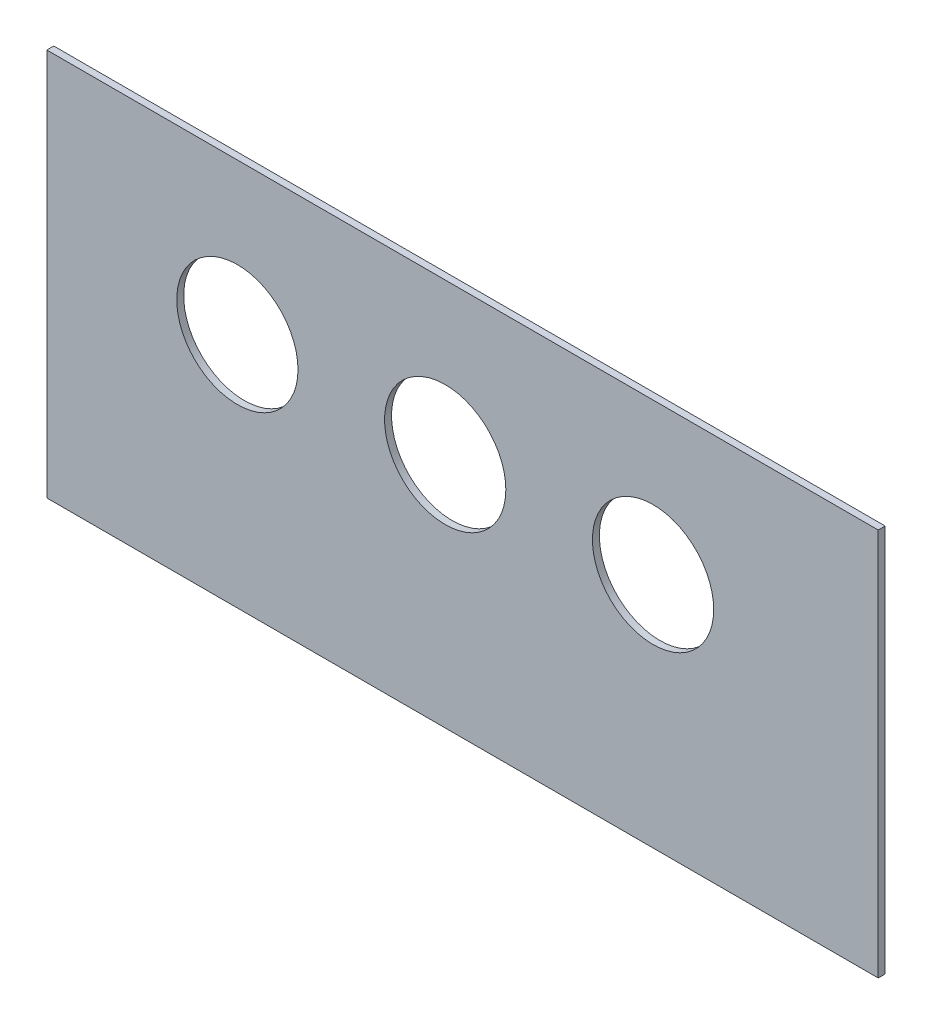
SolidWorks part; units mm, degrees
ref_plane "Front Plane" through (0, 0, 0) normal (0, 0, 1) x (1, 0, 0)
ref_plane "Top Plane" through (0, 0, 0) normal (0, 1, 0) x (1, 0, 0)
ref_plane "Right Plane" through (0, 0, 0) normal (1, 0, 0) x (0, 0, -1)
sketch "Sketch1" plane through (0, 0, 0) normal (0, 0, 1) x (1, 0, 0)
  line L1 (-725, 218.2229) -> (475, 218.2229)
  line L2 (-725, 218.2229) -> (-725, -341.7771)
  line L3 (-725, -341.7771) -> (475, -341.7771)
  line L4 (475, 218.2229) -> (475, -341.7771)
  circle A1 centre (150, 0) radius 87.5
  circle A2 centre (-150, 0) radius 87.5
  circle A4 centre (-450, 0) radius 87.5
  dimension "D3" = 175
  dimension "D4" = 300
  dimension "D5" = 175
  dimension "D10" = 175
  dimension "D1" = 1200
  dimension "D2" = 560
  dimension "D6" = 300
extrude "Boss-Extrude1" add sketch "Sketch1" along normal blind 10
